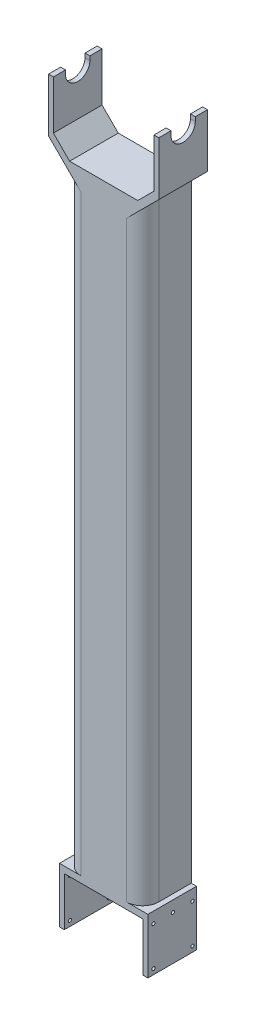
SolidWorks part; units mm, degrees
ref_plane "Front Plane" through (0, 0, 0) normal (0, 0, 1) x (1, 0, 0)
ref_plane "Top Plane" through (0, 0, 0) normal (0, 1, 0) x (1, 0, 0)
ref_plane "Right Plane" through (0, 0, 0) normal (1, 0, 0) x (0, 0, -1)
sketch "Sketch2" plane through (0, 0, 0) normal (0, 1, 0) x (1, 0, 0)
  line L0 (0, 17.205) -> (0, -22.9917) construction
  line L1 (-35.2367, 0) -> (37.9233, 0) construction
  line L2 (-31, 15) -> (31, 15)
  line L3 (31, 15) -> (31, -15)
  line L4 (16, 15) -> (16, -15)
  line L5 (-31, 15) -> (-31, -15)
  line L6 (-16, 15) -> (-16, -15)
  line L7 (-31, -15) -> (31, -15)
  point P11 (0, -15)
  point P14 (0, 15)
  point P15 (31, 0)
  point P16 (16, 0)
  point P17 (-16, 0)
  point P18 (-31, 0)
  dimension "D1" = 31
  dimension "D2" = 15
  dimension "D3" = 15
extrude "Boss-Extrude1" add sketch "Sketch2" along normal blind 3 contours L6 L7 L4 L2 | L5 L7 L6 L2 | L4 L7 L3 L2
sketch "Sketch4" plane through (0, 3, 0) normal (0, 1, 0) x (1, 0, 0)
  line L0 (-31, 15) -> (-31, -15)
  line L1 (-31, 15) -> (-34, 15)
  line L2 (-31, -15) -> (-34, -15)
  line L3 (-34, 15) -> (-34, -15)
  line L4 (31, 15) -> (31, -15)
  line L5 (31, 15) -> (34, 15)
  line L6 (31, -15) -> (34, -15)
  line L7 (34, 15) -> (34, -15)
  dimension "D1" = 3
  dimension "D2" = 3
extrude "Boss-Extrude2" add sketch "Sketch4" against normal blind 3
sketch "Sketch5" plane through (0, 3, 0) normal (0, 1, 0) x (1, 0, 0)
  line L0 (-34, -15) -> (34, -15) construction
  line L1 (-34, 15) -> (-31, 15)
  line L2 (-34, 15) -> (-34, -15)
  line L3 (-34, -15) -> (-31, -15)
  line L4 (-31, 15) -> (-31, -15)
  line L6 (34, 15) -> (31, 15)
  line L7 (34, 15) -> (34, -15)
  line L8 (34, -15) -> (31, -15)
  line L9 (31, 15) -> (31, -15)
  dimension "D1" = 3
  dimension "D2" = 3
extrude "Boss-Extrude3" add sketch "Sketch5" along normal blind 40
sketch "Sketch6" plane through (-34, 0, 0) normal (-1, 0, 0) x (0, 0, 1)
  line L0 (-15, 43) -> (15, 43) construction
  line L1 (-7.5, 45.5) -> (7.5, 45.5)
  line L2 (-7.5, 45.5) -> (-7.5, 40.5)
  line L4 (7.5, 45.5) -> (7.5, 40.5)
  line L5 (-7.5, 45.5) -> (7.5, 40.5) construction
  line L6 (-7.5, 40.5) -> (7.5, 45.5) construction
  arc A0 (-7.5, 40.5) -> (7.5, 40.5) centre (0, 40.5) ccw
  point P0 (0, 43)
  point P8 (0, 33)
  dimension "D1" = 15
  dimension "D2" = 10
extrude "Cut-Extrude1" cut sketch "Sketch6" against normal through all both and the other way through all
chamfer "Chamfer1" distance 10 angle 45 4 edges at (34, 0, 0) (-34, 0, 0) (-31, 3, 0) (31, 3, 0)
sketch "Sketch7" plane through (0, 0, 0) normal (0, -1, 0) x (1, 0, 0)
  line L0 (-24, 15) -> (24, 15)
  line L1 (-24, 15) -> (-24, -15.0235)
  line L2 (24, 15) -> (24, -15.0235)
  line L3 (-24, -15.0235) -> (-19, -15.0235)
  line L4 (-19, -15.0235) -> (-19, 10)
  line L5 (-19, 10) -> (19, 10)
  line L6 (19, 10) -> (19, -15.0235)
  line L7 (19, -15.0235) -> (24, -15.0235)
  dimension "D1" = 5
  dimension "D2" = 5
  dimension "D3" = 5
extrude "Boss-Extrude4" add sketch "Sketch7" along normal blind 375
fillet "Fillet2" radius 10 2 edges at (24, -187.5, 15) (-24, -187.5, 15)
sketch "Sketch8" plane through (0, -375, 0) normal (0, -1, 0) x (1, 0, 0)
  line L1 (-27.25, 15) -> (27.25, 15)
  line L2 (-27.25, 15) -> (-27.25, -15)
  line L3 (-27.25, -15) -> (27.25, -15)
  line L4 (27.25, 15) -> (27.25, -15)
  line L5 (-27.25, 15) -> (27.25, -15) construction
  line L6 (-27.25, -15) -> (27.25, 15) construction
  point P0 (0, 0)
  dimension "D1" = 54.5
  dimension "D2" = 30
extrude "Boss-Extrude5" add sketch "Sketch8" along normal blind 4
sketch "Sketch9" plane through (0, -379, 0) normal (0, -1, 0) x (1, 0, 0)
  line L0 (-27.25, 15) -> (-24.25, 15)
  line L1 (-27.25, 15) -> (-27.25, -15)
  line L2 (-24.25, 15) -> (-24.25, -15)
  line L3 (-27.25, -15) -> (-24.25, -15)
  line L4 (27.25, 15) -> (-27.25, 15) construction
  line L5 (-27.25, -15) -> (27.25, -15) construction
  line L6 (27.25, 15) -> (24.25, 15)
  line L7 (27.25, 15) -> (27.25, -15)
  line L8 (24.25, 15) -> (24.25, -15)
  line L9 (27.25, -15) -> (24.25, -15)
  dimension "D1" = 3
  dimension "D2" = 3
extrude "Boss-Extrude6" add sketch "Sketch9" along normal blind 30
sketch "Sketch10" plane through (-27.25, 0, 0) normal (-1, 0, 0) x (0, 0, 1)
  circle A0 centre (-12.4511, -405.7211) radius 1
  circle A1 centre (11.5489, -405.7211) radius 1
  circle A2 centre (-12.4511, -381.7211) radius 1
  circle A3 centre (11.5489, -381.7211) radius 1
  circle A4 centre (-0.4511, -381.7211) radius 1
  dimension "D1" = 2
  dimension "D2" = 2
  dimension "D4" = 2
  dimension "D5" = 2
  dimension "D8" = 2
  dimension "D3" = 24
  dimension "D6" = 24
  dimension "D7" = 24
  dimension "D9" = 12
extrude "Cut-Extrude2" cut sketch "Sketch10" against normal through all both and the other way through all
